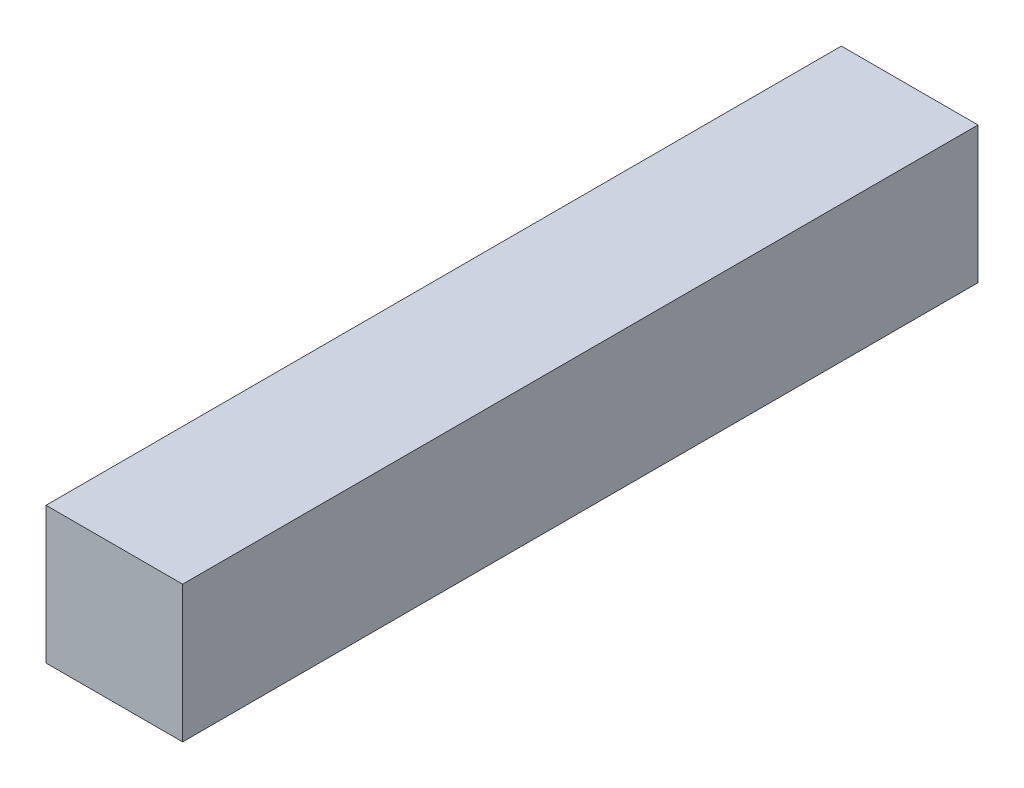
SolidWorks part; units mm, degrees
ref_plane "Front Plane" through (0, 0, 0) normal (0, 0, 1) x (1, 0, 0)
ref_plane "Top Plane" through (0, 0, 0) normal (0, 1, 0) x (1, 0, 0)
ref_plane "Right Plane" through (0, 0, 0) normal (1, 0, 0) x (0, 0, -1)
sketch "Sketch1" plane through (0, 0, 0) normal (0, 0, 1) x (1, 0, 0)
  line L1 (-13.0909, -13.0909) -> (13.0909, -13.0909)
  line L2 (-13.0909, -13.0909) -> (-13.0909, 13.0909)
  line L3 (-13.0909, 13.0909) -> (13.0909, 13.0909)
  line L4 (13.0909, -13.0909) -> (13.0909, 13.0909)
  line L5 (-13.0909, -13.0909) -> (13.0909, 13.0909) construction
  line L6 (-13.0909, 13.0909) -> (13.0909, -13.0909) construction
  point P0 (0, 0)
  dimension "D1" = 26.1817
extrude "Boss-Extrude1" add sketch "Sketch1" along normal mid plane 152.4
